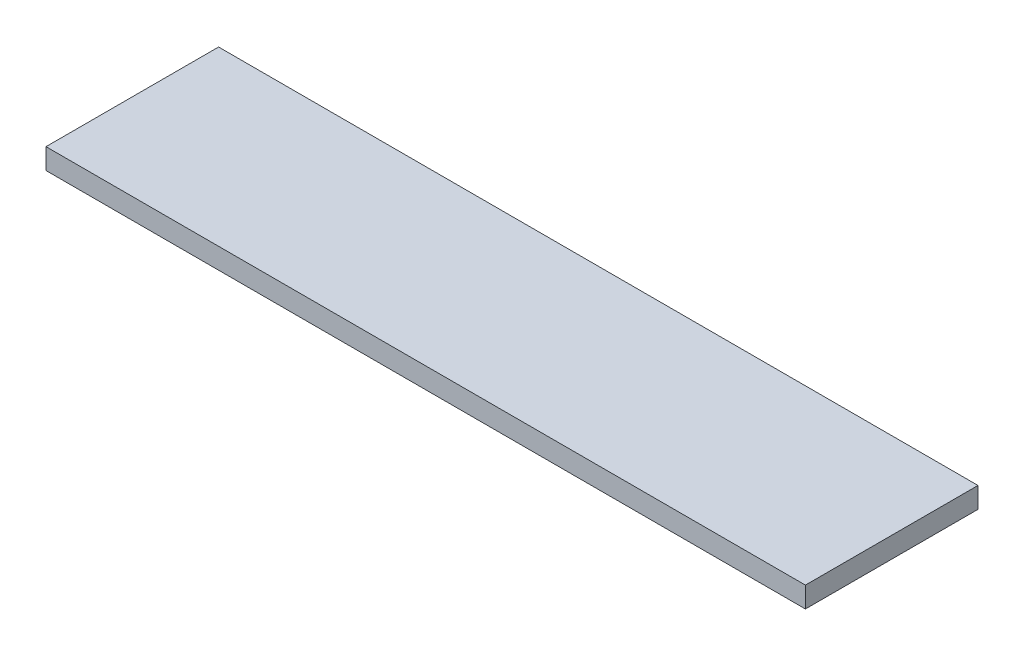
SolidWorks part; units mm, degrees
ref_plane "Front Plane" through (0, 0, 0) normal (0, 0, 1) x (1, 0, 0)
ref_plane "Top Plane" through (0, 0, 0) normal (0, 1, 0) x (1, 0, 0)
ref_plane "Right Plane" through (0, 0, 0) normal (1, 0, 0) x (0, 0, -1)
sketch "Sketch1" plane through (0, 0, 0) normal (0, 1, 0) x (1, 0, 0)
  line L1 (-55, -12.5) -> (55, -12.5)
  line L2 (-55, -12.5) -> (-55, 12.5)
  line L3 (-55, 12.5) -> (55, 12.5)
  line L4 (55, -12.5) -> (55, 12.5)
  line L5 (-55, -12.5) -> (55, 12.5) construction
  line L6 (-55, 12.5) -> (55, -12.5) construction
  point P0 (0, 0)
  dimension "D1" = 110
  dimension "D2" = 25
extrude "Boss-Extrude1" add sketch "Sketch1" along normal blind 3
